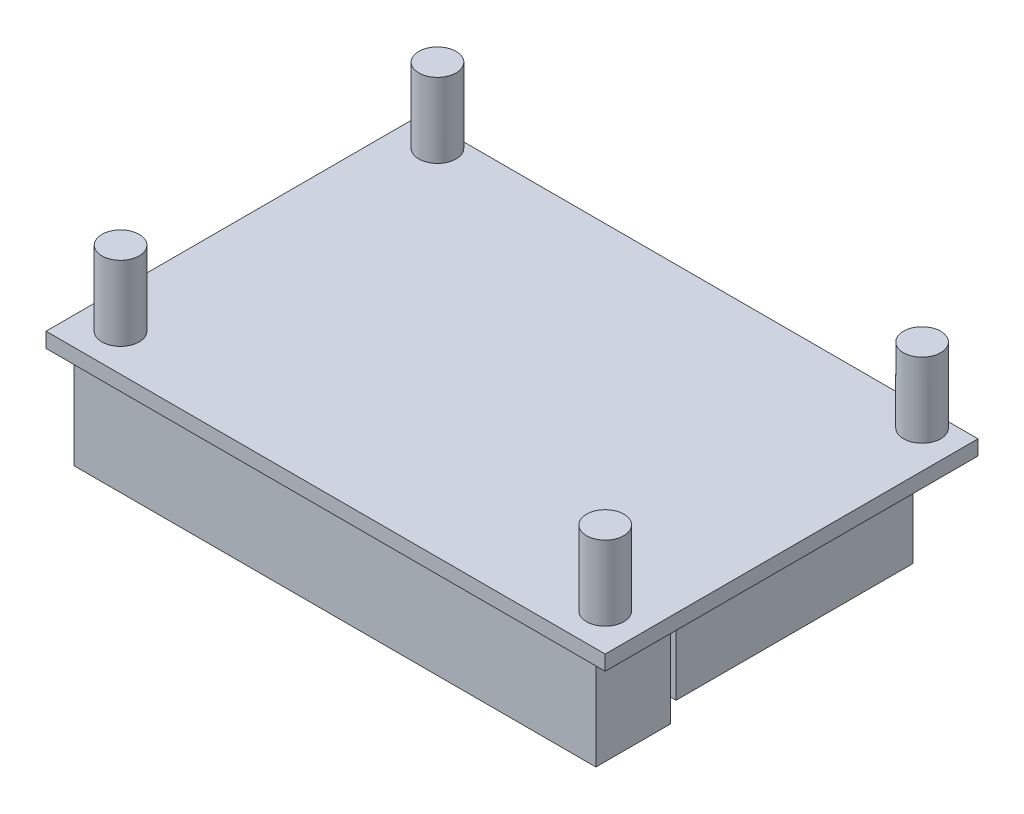
SolidWorks part; units mm, degrees
ref_plane "Front Plane" through (0, 0, 0) normal (0, 0, 1) x (1, 0, 0)
ref_plane "Top Plane" through (0, 0, 0) normal (0, 1, 0) x (1, 0, 0)
ref_plane "Right Plane" through (0, 0, 0) normal (1, 0, 0) x (0, 0, -1)
sketch "SK_P01_Standoff" plane through (0, 0, 0) normal (0, 1, 0) x (1, 0, 0)
  circle A0 centre (-26, 18) radius 2
extrude "P01_Standoff" add sketch "SK_P01_Standoff" along normal blind 8 from offset 14.3
sketch "SK_P02_Standoff" plane through (0, 0, 0) normal (0, 1, 0) x (1, 0, 0)
  circle A0 centre (-26, -16) radius 2
extrude "P02_Standoff" add sketch "SK_P02_Standoff" along normal blind 8 from offset 14.3
sketch "SK_P03_Standoff" plane through (0, 0, 0) normal (0, 1, 0) x (1, 0, 0)
  circle A0 centre (26, 18) radius 2
extrude "P03_Standoff" add sketch "SK_P03_Standoff" along normal blind 8 from offset 14.3
sketch "SK_P04_Standoff" plane through (0, 0, 0) normal (0, 1, 0) x (1, 0, 0)
  circle A0 centre (26, -16) radius 2
extrude "P04_Standoff" add sketch "SK_P04_Standoff" along normal blind 8 from offset 14.3
sketch "SK_P05_Carrierboard" plane through (0, 0, 0) normal (0, 1, 0) x (1, 0, 0)
  line L0 (-30, -20) -> (30, -20)
  line L1 (30, -20) -> (30, 20)
  line L2 (30, 20) -> (-30, 20)
  line L3 (-30, 20) -> (-30, -20)
extrude "P05_Carrierboard" add sketch "SK_P05_Carrierboard" along normal blind 1.6 from offset 12.7
sketch "SK_P06_INA2603sensor" plane through (0, 0, 0) normal (0, 1, 0) x (1, 0, 0)
  line L0 (-28, -7) -> (-5.1, -7)
  line L1 (-5.1, -7) -> (-5.1, 16)
  line L2 (-5.1, 16) -> (-28, 16)
  line L3 (-28, 16) -> (-28, -7)
extrude "P06_INA2603sensor" add sketch "SK_P06_INA2603sensor" along normal blind 2.7 from offset 10
sketch "SK_P07_INA260terminalblock" plane through (0, 0, 0) normal (0, 1, 0) x (1, 0, 0)
  line L0 (-25, 6) -> (-15, 6)
  line L1 (-15, 6) -> (-15, 14)
  line L2 (-15, 14) -> (-25, 14)
  line L3 (-25, 14) -> (-25, 6)
extrude "P07_INA260terminalblock" add sketch "SK_P07_INA260terminalblock" along normal blind 10
sketch "SK_P08_BuckBD36V50F55V" plane through (0, 0, 0) normal (0, 1, 0) x (1, 0, 0)
  line L0 (1.6, -9.4) -> (27, -9.4)
  line L1 (27, -9.4) -> (27, 16)
  line L2 (27, 16) -> (1.6, 16)
  line L3 (1.6, 16) -> (1.6, -9.4)
extrude "P08_BuckBD36V50F55V" add sketch "SK_P08_BuckBD36V50F55V" along normal blind 9.5 from offset 3.2
sketch "SK_P09_JSTXHheadersfacedown" plane through (0, 0, 0) normal (0, 1, 0) x (1, 0, 0)
  line L0 (-28, -19) -> (28, -19)
  line L1 (28, -19) -> (28, -11)
  line L2 (28, -11) -> (-28, -11)
  line L3 (-28, -11) -> (-28, -19)
extrude "P09_JSTXHheadersfacedown" add sketch "SK_P09_JSTXHheadersfacedown" along normal blind 10.4 from offset 2.3
